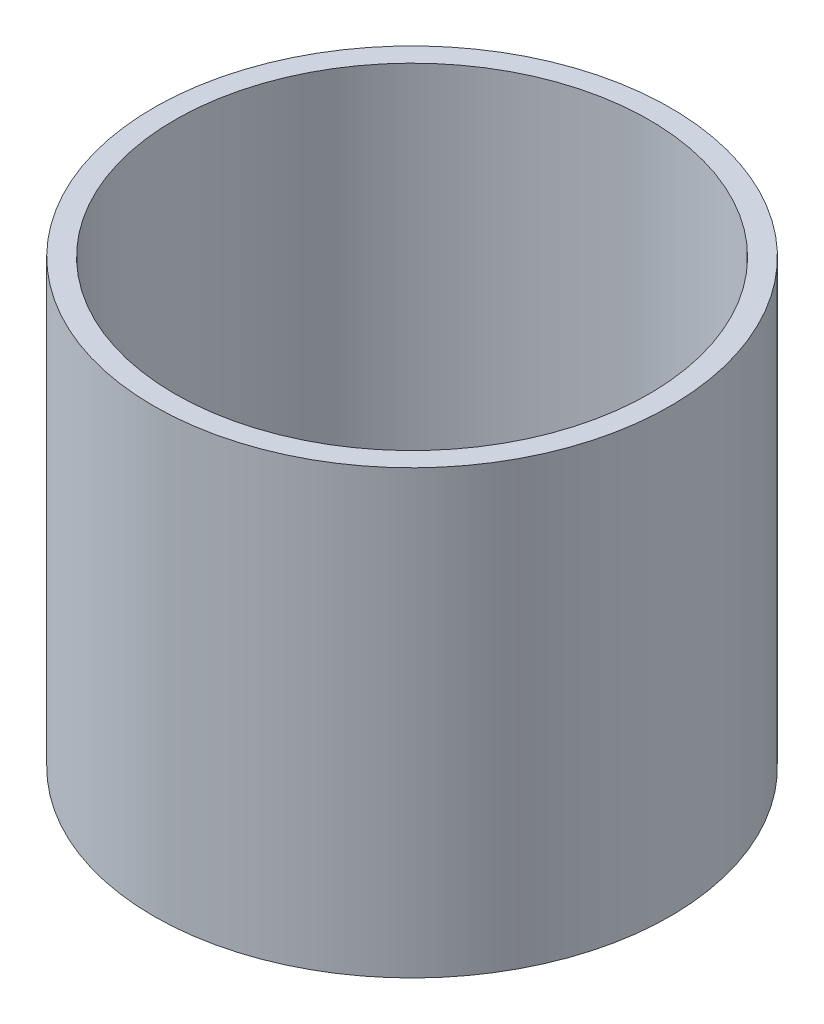
SolidWorks part; units mm, degrees
material "6061-T6 (SS)"
ref_plane "Front Plane" through (0, 0, 0) normal (0, 0, 1) x (1, 0, 0)
ref_plane "Top Plane" through (0, 0, 0) normal (0, 1, 0) x (1, 0, 0)
ref_plane "Right Plane" through (0, 0, 0) normal (1, 0, 0) x (0, 0, -1)
sketch "Sketch1" plane through (0, 0, 0) normal (0, 1, 0) x (1, 0, 0)
  circle A0 centre (0, 0) radius 24.5
  circle A1 centre (0, 0) radius 22.5
  dimension "D1" = 49
  dimension "D2" = 45
extrude "Boss-Extrude1" add sketch "Sketch1" along normal blind 41.9
